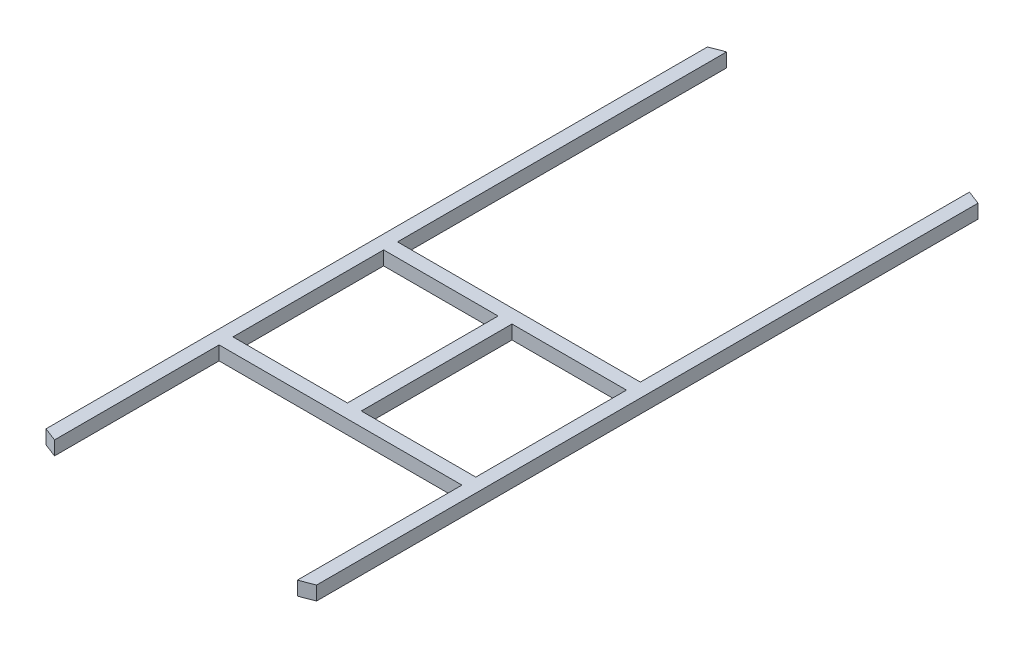
SolidWorks part; units mm, degrees
ref_plane "前视基准面" through (0, 0, 0) normal (0, 0, 1) x (1, 0, 0)
ref_plane "上视基准面" through (0, 0, 0) normal (0, 1, 0) x (1, 0, 0)
ref_plane "右视基准面" through (0, 0, 0) normal (1, 0, 0) x (0, 0, -1)
other "Configuration Table"
sketch "草图1" plane through (0, 0, 0) normal (0, 1, 0) x (1, 0, 0)
  line L0 (0, 0) -> (0, 95.33)
  line L1 (0, 95.33) -> (4, 96.87)
  line L2 (4, 96.87) -> (4, -96.87) construction
  line L3 (4, -96.87) -> (0, -95.33)
  line L4 (0, -95.33) -> (0, 0)
  line L5 (74, 96.87) -> (74, 2)
  line L6 (74, -96.87) -> (78, -95.33)
  line L7 (78, -95.33) -> (78, 95.33)
  line L8 (78, 95.33) -> (74, 96.87)
  line L9 (4, 0) -> (4, -2) construction
  line L10 (4, -2) -> (37, -2)
  line L12 (74, 2) -> (4, 2)
  line L13 (4, 2) -> (4, -2) construction
  line L14 (74, -2) -> (74, -96.87) construction
  line L15 (4, -96.87) -> (4, -2) construction
  line L16 (4, 2) -> (4, 96.87)
  line L17 (4, -49.435) -> (74, -49.435)
  line L19 (74, -45.435) -> (41, -45.435)
  line L21 (4, -2) -> (4, -45.435)
  line L22 (4, -49.435) -> (4, -96.87)
  line L23 (74, -2) -> (74, -45.435)
  line L24 (74, -49.435) -> (74, -96.87)
  line L25 (37, -2) -> (37, -45.435)
  line L26 (41, -2) -> (41, -45.435)
  line L27 (37, -45.435) -> (4, -45.435)
  line L28 (41, -2) -> (74, -2)
  dimension "D1" = 193.74
  dimension "D2" = 4
  dimension "D3" = 190.66
  dimension "D4" = 4
  dimension "D5" = 70
  dimension "D6" = 190.66
  dimension "D7" = 193.74
  dimension "D8" = 70
  dimension "D9" = 2
  dimension "D10" = 4
  dimension "D11" = 4
  dimension "D12" = 4
  dimension "D13" = 33
extrude "凸台-拉伸1" add sketch "草图1" along normal blind 4
